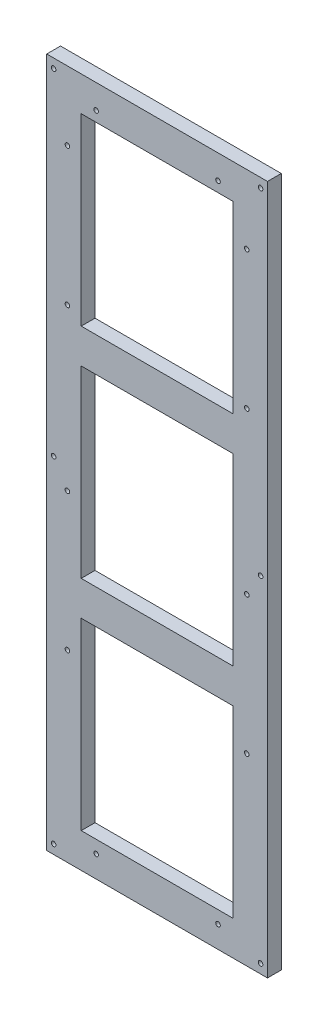
SolidWorks part; units mm, degrees
material "Alumina"
ref_plane "Front Plane" through (0, 0, 0) normal (0, 0, 1) x (1, 0, 0)
ref_plane "Top Plane" through (0, 0, 0) normal (0, 1, 0) x (1, 0, 0)
ref_plane "Right Plane" through (0, 0, 0) normal (1, 0, 0) x (0, 0, -1)
sketch "Sketch1" plane through (0, 0, 0) normal (0, 0, 1) x (1, 0, 0)
  line L0 (33, 141) -> (33, 61)
  line L9 (-48, -144) -> (48, -144)
  line L10 (-48, -144) -> (-48, 156)
  line L11 (-48, 156) -> (48, 156)
  line L12 (48, -144) -> (48, 156)
  line L14 (0, 0) -> (0, 46) construction
  line L15 (-33, -129) -> (33, -129)
  line L17 (-33, 141) -> (33, 141)
  line L19 (-33, 46) -> (-33, -34)
  line L20 (-33, -49) -> (-33, -129)
  line L21 (-33, 61) -> (33, 61)
  line L23 (-33, 46) -> (33, 46)
  line L25 (-33, -34) -> (33, -34)
  line L27 (-33, -49) -> (33, -49)
  line L33 (33, 46) -> (33, -34)
  line L34 (-33, 61) -> (-33, 141)
  line L36 (33, -49) -> (33, -129)
  dimension "D1" = 96
  dimension "D2" = 15
  dimension "D3" = 66
  dimension "D4" = 80
  dimension "D5" = 15
  dimension "D6" = 80
  dimension "D7" = 15
  dimension "D8" = 80
  dimension "D9" = 46
  dimension "D10" = 15
  dimension "D12" = 15
extrude "Boss-Extrude1" add sketch "Sketch1" along normal blind 6
sketch "Sketch3" plane through (0, 0, 6) normal (0, 0, 1) x (1, 0, 0)
  line L0 (48, 156) -> (-48, 156) construction
  line L1 (-48, 156) -> (-48, -144) construction
  line L2 (0, -3.3) -> (0, 3.3) construction
  line L3 (-48, -144) -> (48, -144) construction
  circle A0 centre (-39, 126) radius 1
  circle A26 centre (-39, -4) radius 1
  circle A29 centre (-39, 66) radius 1
  circle A33 centre (-39, -64) radius 1
  circle A41 centre (39, -64) radius 1
  circle A42 centre (39, -4) radius 1
  circle A43 centre (39, 66) radius 1
  circle A44 centre (39, 126) radius 1
  dimension "D1" = 30
  dimension "D6" = 9
  dimension "D3" = 2
  dimension "D8" = 9
  dimension "D9" = 9
  dimension "D10" = 2
  dimension "D12" = 2
  dimension "D14" = 9
  dimension "D4" = 2
  dimension "D2" = 60
  dimension "D7" = 70
  dimension "D5" = 80
extrude "Cut-Extrude6" cut sketch "Sketch3" against normal blind 10
ref_plane "Plane1" through (0, 6, 0) normal (0, 1, 0) x (1, 0, 0)
sketch "Sketch5" plane through (0, 0, 6) normal (0, 0, 1) x (1, 0, 0)
  line L0 (-26.5, 145.5) -> (26.5, 145.5) construction
  line L1 (26.5, 145.5) -> (26.5, -134.5) construction
  line L2 (26.5, -134.5) -> (-26.5, -134.5) construction
  line L3 (-26.5, -134.5) -> (-26.5, 145.5) construction
  line L4 (48, 156) -> (-48, 156) construction
  line L5 (-48, -144) -> (48, -144) construction
  line L6 (48, -144) -> (48, 156) construction
  line L7 (-48, 156) -> (-48, -144) construction
  circle A0 centre (-26.5, -134.5) radius 1
  circle A1 centre (26.5, -134.5) radius 1
  circle A2 centre (-26.5, 145.5) radius 1
  circle A3 centre (26.5, 145.5) radius 1
  dimension "D5" = 2
  dimension "D6" = 2
  dimension "D7" = 2
  dimension "D8" = 2
  dimension "D1" = 10.5
  dimension "D2" = 9.5
  dimension "D3" = 21.5
  dimension "D4" = 21.5
extrude "Cut-Extrude9" cut sketch "Sketch5" against normal blind 10
sketch "Sketch7" plane through (0, 0, 6) normal (0, 0, 1) x (1, 0, 0)
  line L0 (-45, 152) -> (45, 152) construction
  line L1 (45, 152) -> (45, -140) construction
  line L2 (45, -140) -> (-45, -140) construction
  line L3 (-45, -140) -> (-45, 152) construction
  line L4 (-48, 156) -> (-48, -144) construction
  line L5 (48, -144) -> (48, 156) construction
  line L6 (48, 156) -> (-48, 156) construction
  line L7 (-48, -144) -> (48, -144) construction
  line L8 (-33, -34) -> (33, 46) construction
  line L9 (-33, 46) -> (-33, -34) construction
  line L10 (33, 46) -> (-33, 46) construction
  line L11 (-33, 46) -> (33, -34) construction
  line L12 (-33, -34) -> (33, -34) construction
  line L13 (-45, 6) -> (45, 6) construction
  circle A0 centre (45, -140) radius 1
  circle A1 centre (-45, -140) radius 1
  circle A2 centre (45, 152) radius 1
  circle A3 centre (-45, 152) radius 1
  circle A4 centre (45, 6) radius 1
  circle A5 centre (-45, 6) radius 1
  point P20 (44.7895, 6)
  point P31 (-45, 6)
  point P32 (-44, 6)
  dimension "D5" = 2
  dimension "D6" = 2
  dimension "D7" = 2
  dimension "D8" = 2
  dimension "D9" = 2
  dimension "D10" = 2
  dimension "D1" = 3
  dimension "D2" = 3
  dimension "D3" = 4
  dimension "D4" = 4
extrude "Cut-Extrude10" cut sketch "Sketch7" against normal blind 10
